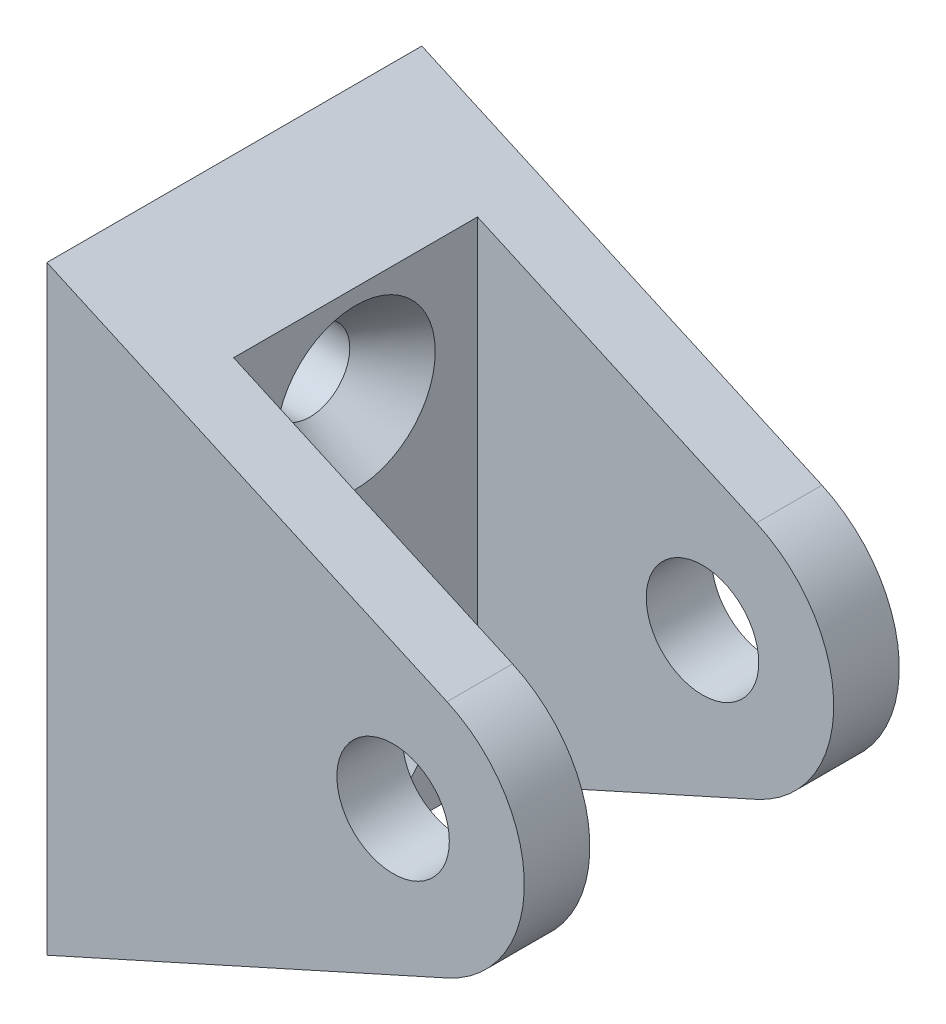
SolidWorks part; units mm, degrees
ref_plane "Front Plane" through (0, 0, 0) normal (0, 0, 1) x (1, 0, 0)
ref_plane "Top Plane" through (0, 0, 0) normal (0, 1, 0) x (1, 0, 0)
ref_plane "Right Plane" through (0, 0, 0) normal (1, 0, 0) x (0, 0, -1)
sketch "Sketch1" plane through (0, 0, 0) normal (0, 1, 0) x (1, 0, 0)
  line L0 (0, 0) -> (42.0157, 0)
  line L1 (42.0157, 0) -> (42.0157, 5.5499)
  line L2 (42.0157, 5.5499) -> (10.2657, 5.5499)
  line L3 (10.2657, 5.5499) -> (10.2657, 26.2001)
  line L4 (10.2657, 26.2001) -> (42.0157, 26.2001)
  line L5 (42.0157, 26.2001) -> (42.0157, 31.75)
  line L6 (42.0157, 31.75) -> (0, 31.75)
  line L7 (0, 31.75) -> (0, 0)
  line L8 (29.3157, 31.75) -> (29.3157, 0) construction
  circle A0 centre (29.3157, 15.875) radius 10.3505 construction
  point P13 (44.4839, 25.4)
  dimension "D4" = 20.701
  dimension "D1" = 31.75
  dimension "D2" = 31.75
  dimension "D3" = 20.6502
  dimension "D5" = 12.7
extrude "Camber Block Extrude" add sketch "Sketch1" along normal blind 50.8
sketch "Sketch2" plane through (10.2657, 0, 0) normal (1, 0, 0) x (0, 0, -1)
  line L0 (5.5499, 25.4) -> (26.2001, 25.4) construction
  line L1 (5.5499, 50.8) -> (5.5499, 0) construction
  line L2 (26.2001, 50.8) -> (26.2001, 0) construction
  line L3 (15.875, 38.1) -> (15.875, 12.7) construction
  circle A0 centre (15.875, 38.1) radius 3.175 construction
  circle A1 centre (15.875, 12.7) radius 3.175 construction
  point P6 (15.875, 38.1)
  point P7 (15.875, 12.7)
  point P10 (15.875, 25.4)
  point P12 (15.875, 25.4)
  point P17 (15.875, 38.1)
  point P19 (15.875, 12.7)
  dimension "D2" = 6.35
  dimension "D3" = 6.35
  dimension "D1" = 25.4
hole_wizard "CSK for 1/4 Flat Head Machine Screw (100)1" positions "Sketch2" profile "Sketch3" countersink size "1/4" standard "ANSI Inch" end condition through all
sketch "Sketch3" plane through (10.2657, 12.7, -15.875) normal (0, 1, 0) x (0, 0, -1)
  line L0 (0, 0) -> (0, 10.2657)
  line L1 (0, 10.2657) -> (3.3782, 10.2657)
  line L2 (3.3782, 10.2657) -> (3.3782, 3.8716)
  line L3 (3.3782, 3.8716) -> (6.7437, 0)
  line L5 (6.7437, 0) -> (0, 0)
  line L6 (-3.3782, 3.8716) -> (-6.7437, 0) construction
  line L11 (0, -6.35) -> (0, 107.95) construction
  dimension "Thru Hole Dia." = 6.7564
  dimension "Thru Hole Depth" = 10.2657
  dimension "Near C'Sink Dia." = 13.4874
  dimension "Near C'Sink Angle" = 82
sketch "Sketch5" plane through (0, 0, 0) normal (0, 0, 1) x (1, 0, 0)
  line L0 (0, 25.4) -> (42.0157, 25.4) construction
  line L1 (0, 50.8) -> (0, 0) construction
  line L2 (42.0157, 50.8) -> (42.0157, 0) construction
  line L3 (0, 0) -> (33.8813, 15.2688)
  line L4 (0, 50.8) -> (33.8813, 35.5312)
  line L5 (0, 0) -> (42.0157, 0)
  line L6 (42.0157, 0) -> (42.0157, 50.8)
  line L7 (42.0157, 50.8) -> (0, 50.8)
  circle A0 centre (29.3157, 25.4) radius 4.7625
  arc A1 (33.8813, 15.2688) -> (33.8813, 35.5312) centre (29.3157, 25.4) ccw
  dimension "D1" = 9.525
  dimension "D2" = 6.35
extrude "Cut-Extrude1" cut sketch "Sketch5" against normal up to surface (31.75 mm away) up to face at (21.0078, 25.4, -31.75)
